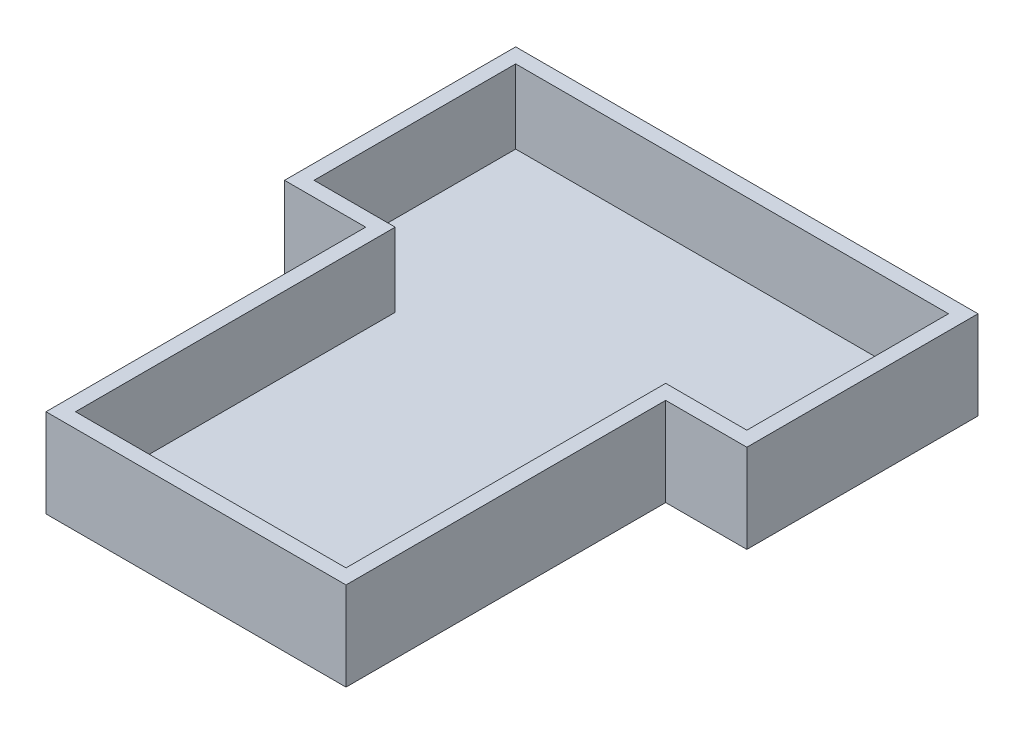
SolidWorks part; units mm, degrees
ref_plane "Front Plane" through (0, 0, 0) normal (0, 0, 1) x (1, 0, 0)
ref_plane "Top Plane" through (0, 0, 0) normal (0, 1, 0) x (1, 0, 0)
ref_plane "Right Plane" through (0, 0, 0) normal (1, 0, 0) x (0, 0, -1)
sketch "Sketch1" plane through (0, 0, 0) normal (0, 1, 0) x (1, 0, 0)
  line L0 (0, 0) -> (88, 0)
  line L1 (88, 0) -> (88, -41)
  line L2 (88, -41) -> (71.5, -41)
  line L3 (71.5, -41) -> (71.5, -106)
  line L4 (71.5, -106) -> (16.5, -106)
  line L5 (16.5, -106) -> (16.5, -41)
  line L6 (16.5, -41) -> (0, -41)
  line L7 (0, -41) -> (0, 0)
  dimension "D1" = 88
  dimension "D2" = 55
  dimension "D3" = 41
  dimension "D4" = 65
extrude "Boss-Extrude1" add sketch "Sketch1" along normal blind 15
shell "Shell1" thickness 3
